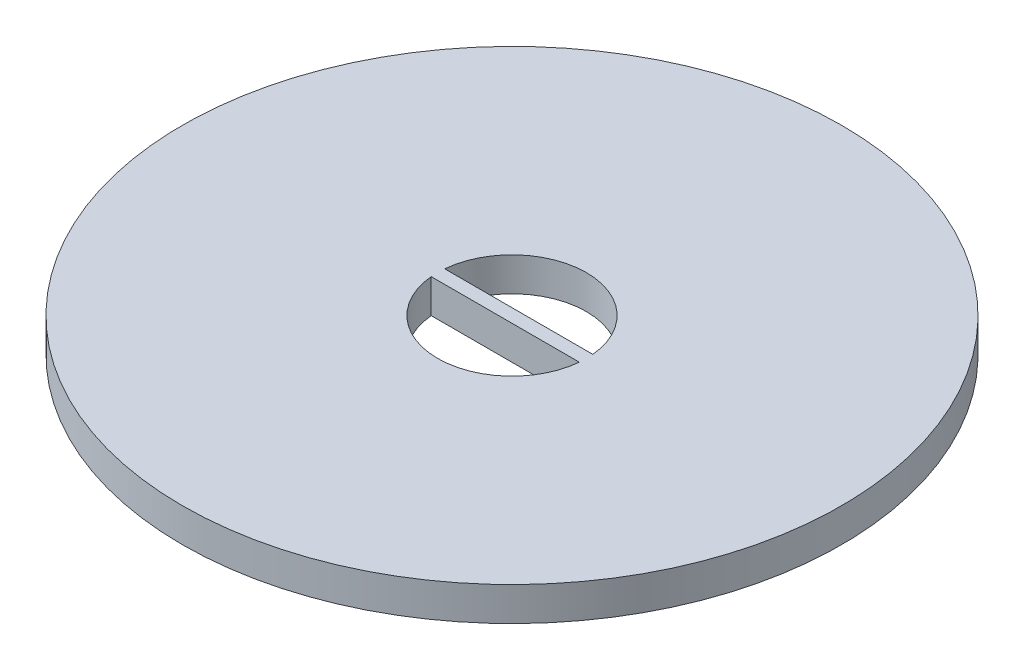
SolidWorks part; units mm, degrees
ref_plane "Front Plane" through (0, 0, 0) normal (0, 0, 1) x (1, 0, 0)
ref_plane "Top Plane" through (0, 0, 0) normal (0, 1, 0) x (1, 0, 0)
ref_plane "Right Plane" through (0, 0, 0) normal (1, 0, 0) x (0, 0, -1)
sketch "Sketch1" plane through (0, 0, 0) normal (0, 1, 0) x (1, 0, 0)
  circle A0 centre (0, 0) radius 9.75
extrude "Boss-Extrude1" add sketch "Sketch1" along normal blind 1
sketch "Sketch2" plane through (0, 1, 0) normal (0, 1, 0) x (1, 0, 0)
  line L0 (0, 0) -> (0, 0.2)
  line L1 (0, 0.2) -> (-3.2284, 0.2)
  line L3 (-3.2284, 0.2) -> (3.1664, 0.2)
  line L4 (-3.2284, 0.2) -> (-3.2284, -0.2)
  line L5 (-3.2284, -0.2) -> (3.1664, -0.2)
  line L6 (3.1664, 0.2) -> (3.1664, -0.2)
  circle A0 centre (0, 0) radius 2.2
extrude "Cut-Extrude1" cut sketch "Sketch2" against normal blind 3 contours L3 A0 L1 | L5 A0
